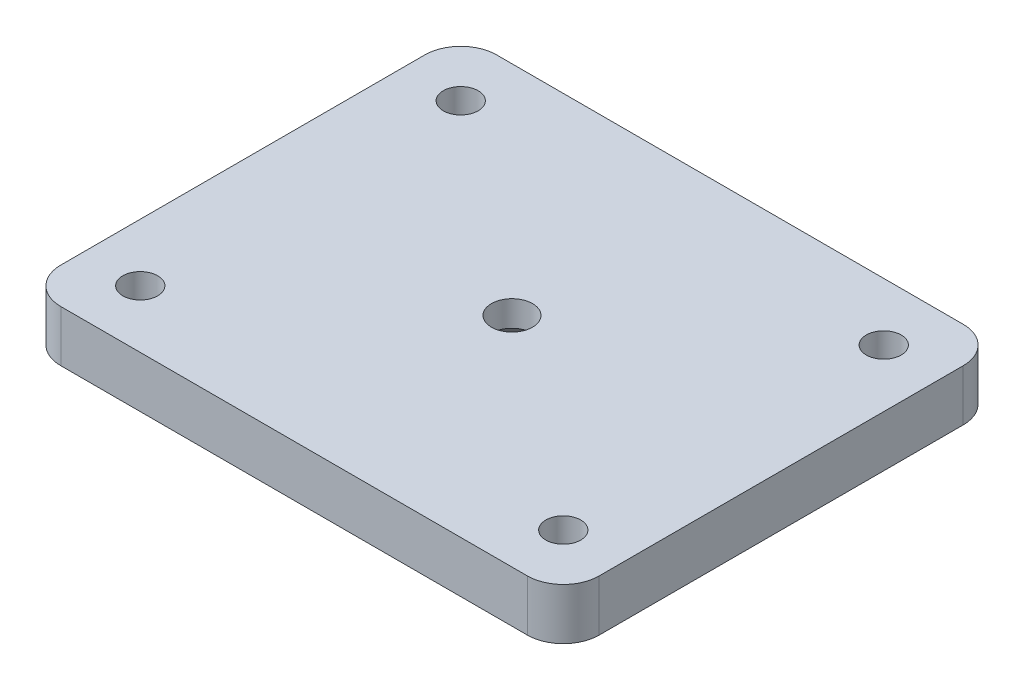
SolidWorks part; units mm, degrees
ref_plane "Front Plane" through (0, 0, 0) normal (0, 0, 1) x (1, 0, 0)
ref_plane "Top Plane" through (0, 0, 0) normal (0, 1, 0) x (1, 0, 0)
ref_plane "Right Plane" through (0, 0, 0) normal (1, 0, 0) x (0, 0, -1)
sketch "Sketch2" plane through (0, 0, 0) normal (0, 1, 0) x (1, 0, 0)
  line L1 (-52.5, -42.5) -> (52.5, -42.5)
  line L2 (-52.5, -42.5) -> (-52.5, 42.5)
  line L3 (-52.5, 42.5) -> (52.5, 42.5)
  line L4 (52.5, -42.5) -> (52.5, 42.5)
  line L5 (-52.5, -42.5) -> (52.5, 42.5) construction
  line L6 (-52.5, 42.5) -> (52.5, -42.5) construction
  point P0 (0, 0)
  dimension "D1" = 105
  dimension "D2" = 85
extrude "Boss-Extrude1" add sketch "Sketch2" along normal blind 10
sketch "Sketch3" plane through (0, 10, 0) normal (0, 1, 0) x (1, 0, 0)
  line L1 (-41.25, -31.25) -> (41.25, -31.25) construction
  line L2 (-41.25, -31.25) -> (-41.25, 31.25) construction
  line L3 (-41.25, 31.25) -> (41.25, 31.25) construction
  line L4 (41.25, -31.25) -> (41.25, 31.25) construction
  line L5 (-41.25, -31.25) -> (41.25, 31.25) construction
  line L6 (-41.25, 31.25) -> (41.25, -31.25) construction
  point P0 (0, 0)
  dimension "D1" = 82.5
  dimension "D2" = 62.5
hole_wizard "caster mounting holes tzpped holes, m8x1.25" positions "Sketch4" profile "Sketch5" tap size "M8" standard "ISO" end condition through all
sketch "Sketch4" plane through (0, 10, 0) normal (0, 1, 0) x (1, 0, 0)
  point P0 (-41.25, 31.25)
  point P3 (-41.25, -31.25)
  point P6 (41.25, -31.25)
  point P9 (41.25, 31.25)
sketch "Sketch5" plane through (-41.25, 10, -31.25) normal (1, 0, 0) x (0, 0, 1)
  line L0 (0, 0) -> (0, 10)
  line L1 (0, 10) -> (3.4, 10)
  line L2 (3.4, 10) -> (3.4, 0)
  line L5 (3.4, 0) -> (0, 0)
  line L11 (0, -6.35) -> (0, 107.95) construction
  dimension "Thru Tap Drill Dia." = 6.8
  dimension "Thru Tap Drill Depth" = 10
cosmetic thread "Hole Thread5"
cosmetic thread "Hole Thread6"
cosmetic thread "Hole Thread7"
cosmetic thread "Hole Thread8"
sketch "profile projection" plane through (0, 0, 0) normal (0, -1, 0) x (1, 0, 0)
  line L1 (-11.6, -11.6) -> (11.6, -11.6) construction
  line L2 (-11.6, -11.6) -> (-11.6, 11.6) construction
  line L3 (-11.6, 11.6) -> (11.6, 11.6) construction
  line L4 (11.6, -11.6) -> (11.6, 11.6) construction
  line L5 (-11.6, -11.6) -> (11.6, 11.6) construction
  line L6 (-11.6, 11.6) -> (11.6, -11.6) construction
  point P0 (0, 0)
  dimension "D1" = 23.2
hole_wizard "corner profile cs holes, m5x08" positions "Sketch17" profile "Sketch19" legacy
sketch "Sketch17" plane through (0, 0, 0) normal (0, -1, 0) x (-1, 0, 0)
  point P0 (11.6, -11.6)
  point P3 (-11.6, -11.6)
  point P6 (-11.6, 11.6)
  point P9 (11.6, 11.6)
sketch "Sketch19" plane through (-11.6, 0, 11.6) normal (1, 0, 0) x (0, 0, -1)
  line L0 (0, 0) -> (0, 11.5022)
  line L1 (0, 11.5022) -> (2.5, 10)
  line L2 (2.5, 10) -> (2.5, 3.1)
  line L3 (2.5, 3.1) -> (5.6, 0)
  line L4 (5.6, 0) -> (0, 0)
  line L5 (0, -14.3089) -> (0, 102.4216) construction
  line L6 (0, 11.5022) -> (-2.5, 10) construction
  line L7 (-2.5, 3.1) -> (-5.6, 0) construction
  dimension "Diameter" = 5
  dimension "Depth" = 10
  dimension "C-Sink Diameter" = 11.2
  dimension "C-Sink Angle" = 90
  dimension "Drill Angle" = 118
hole_wizard "center profile cs hole, m8x1.25" positions "Sketch20" profile "Sketch22" legacy end condition through all
sketch "Sketch20" plane through (0, 0, 0) normal (0, -1, 0) x (-1, 0, 0)
  point P0 (0, 0)
sketch "Sketch22" plane through (0, 0, 0) normal (1, 0, 0) x (0, 0, -1)
  line L0 (0, 0) -> (0, 12.4034)
  line L1 (0, 12.4034) -> (4, 10)
  line L2 (4, 10) -> (4, 5)
  line L3 (4, 5) -> (9, 0)
  line L4 (9, 0) -> (0, 0)
  line L5 (0, -14.3089) -> (0, 102.4216) construction
  line L6 (0, 12.4034) -> (-4, 10) construction
  line L7 (-4, 5) -> (-9, 0) construction
  dimension "Diameter" = 8
  dimension "Depth" = 10
  dimension "C-Sink Diameter" = 18
  dimension "C-Sink Angle" = 90
  dimension "Drill Angle" = 118
fillet "Fillet1" radius 7 4 edges at (-52.5, 5, -42.5) (52.5, 5, -42.5) (52.5, 5, 42.5) (-52.5, 5, 42.5)
hole_wizard "Hole1" positions "Sketch23" profile "Sketch24" legacy
sketch "Sketch23" plane through (0, 10, 0) normal (0, 1, 0) x (1, 0, 0)
  point P0 (-41.25, -31.25)
  point P3 (-41.25, 31.25)
  point P6 (41.25, 31.25)
  point P9 (41.25, -31.25)
sketch "Sketch24" plane through (-41.25, 10, 31.25) normal (1, 0, 0) x (0, 0, 1)
  line L0 (0, 0) -> (0, 10)
  line L1 (0, 10) -> (4, 10)
  line L2 (4, 10) -> (4, 0)
  line L3 (4, 0) -> (0, 0)
  line L4 (0, 110) -> (0, -10) construction
  dimension "Diameter" = 8
  dimension "Depth" = 10
